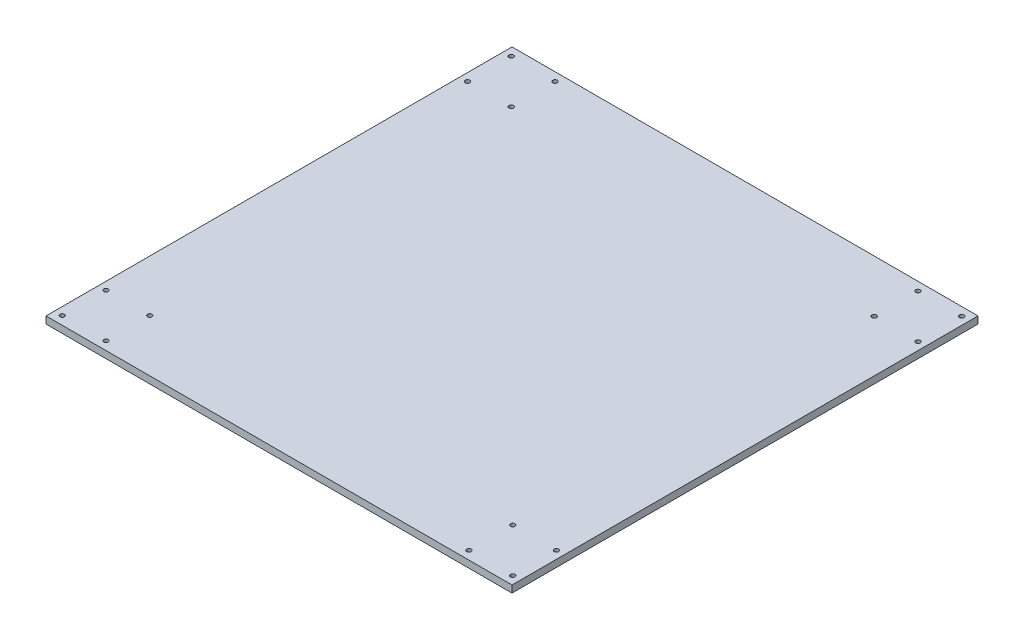
SolidWorks part; units mm, degrees
ref_plane "前视基准面" through (0, 0, 0) normal (0, 0, 1) x (1, 0, 0)
ref_plane "上视基准面" through (0, 0, 0) normal (0, 1, 0) x (1, 0, 0)
ref_plane "右视基准面" through (0, 0, 0) normal (1, 0, 0) x (0, 0, -1)
other "Configuration Table"
sketch "草图1" plane through (0, 0, 0) normal (0, 1, 0) x (1, 0, 0)
  line L1 (165, -165) -> (-165, -165)
  line L2 (165, -165) -> (165, 165)
  line L3 (165, 165) -> (-165, 165)
  line L4 (-165, -165) -> (-165, 165)
  line L5 (165, -165) -> (-165, 165) construction
  line L6 (165, 165) -> (-165, -165) construction
  point P0 (0, 0)
  dimension "D1" = 330
  dimension "D2" = 330
extrude "凸台-拉伸1" add sketch "草图1" along normal blind 5
sketch "草图2" plane through (0, 5, 0) normal (0, 1, 0) x (1, 0, 0)
  circle A0 centre (-159.5, 159) radius 1.6
  circle A1 centre (-128.5, 159) radius 1.6
  circle A2 centre (-159.5, 128) radius 1.6022
  circle A3 centre (-128.5, 128) radius 1.6
  circle A4 centre (128.5, 159) radius 1.6
  circle A5 centre (159.5, 159) radius 1.6
  circle A6 centre (128.5, 128) radius 1.6
  circle A7 centre (159.5, 128) radius 1.6
  circle A8 centre (128.5, -128) radius 1.6
  circle A9 centre (159.5, -128) radius 1.6
  circle A10 centre (159.5, -159) radius 1.6
  circle A11 centre (128.5, -159) radius 1.6
  circle A12 centre (-128.5, -159) radius 1.6
  circle A13 centre (-159.5, -159) radius 1.6
  circle A14 centre (-159.5, -128) radius 1.6
  circle A15 centre (-128.5, -128) radius 1.6
extrude "切除-拉伸1" cut sketch "草图2" against normal through all
